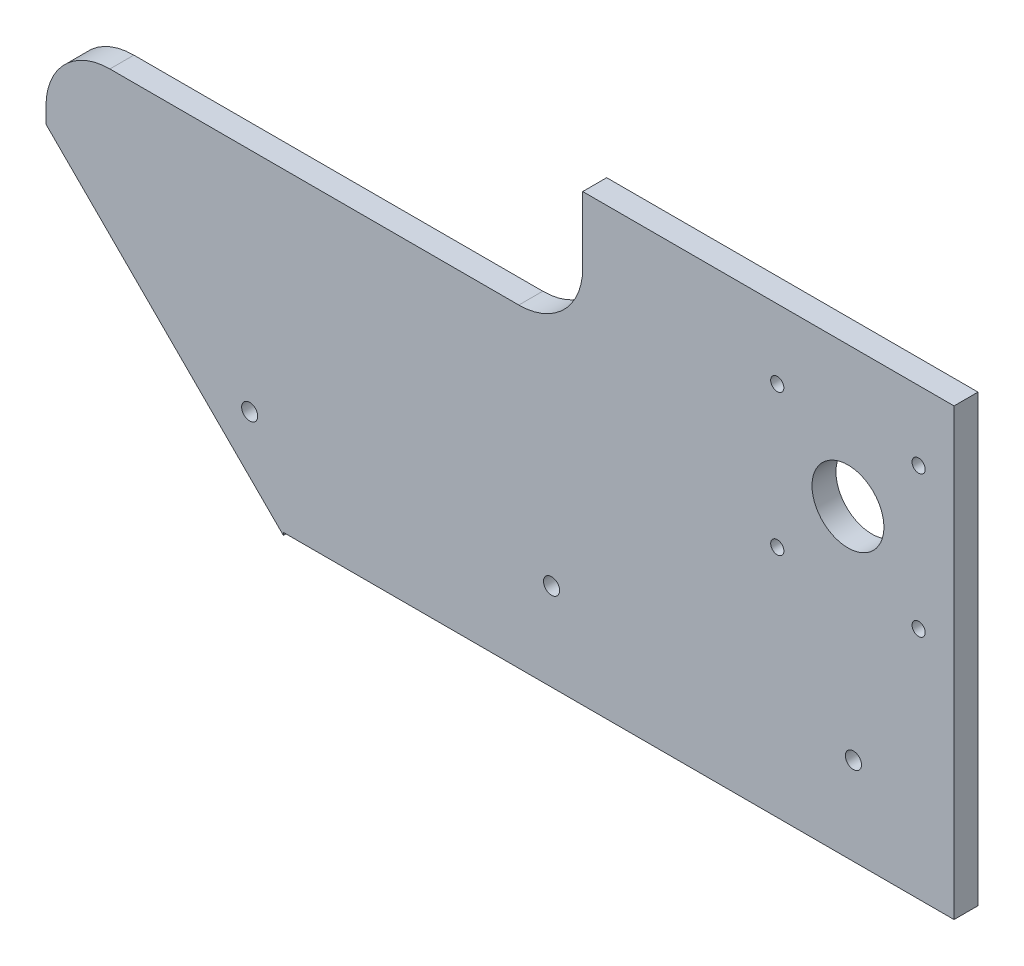
SolidWorks part; units mm, degrees
ref_plane "Front Plane" through (0, 0, 0) normal (0, 0, 1) x (1, 0, 0)
ref_plane "Top Plane" through (0, 0, 0) normal (0, 1, 0) x (1, 0, 0)
ref_plane "Right Plane" through (0, 0, 0) normal (1, 0, 0) x (0, 0, -1)
sketch "Sketch1" plane through (0, 0, 0) normal (0, 0, 1) x (1, 0, 0)
  line L0 (-138.2594, 48.9915) -> (32.2106, -121.4785)
  line L1 (32.2106, -121.4785) -> (222.7106, -121.4785)
  line L2 (-138.2594, 146.2068) -> (-138.2594, 48.9915)
  line L3 (-138.2594, 146.2068) -> (222.7106, 146.2068)
  line L4 (222.7106, -121.4785) -> (222.7106, 146.2068)
  circle A0 centre (180.538, 76.832) radius 14.2875
  circle A2 centre (180.538, 76.832) radius 69.85 construction
  circle A3 centre (180.538, 76.832) radius 318.7974 construction
  point P0 (0, 0)
  point P2 (180.538, 76.832)
  dimension "D4" = 198.3105
  dimension "D1" = 45
  dimension "D2" = 267.6854
  dimension "D5" = 245.11
extrude "Boss-Extrude1" add sketch "Sketch1" along normal blind 9.525
sketch "Sketch2" plane through (0, 0, 9.525) normal (0, 0, 1) x (1, 0, 0)
  line L0 (32.2106, -121.4785) -> (222.7106, -121.4785) construction
  line L1 (241.7606, -121.4785) -> (-43.8796, -121.4785)
  line L2 (241.7606, -121.4785) -> (241.7606, -44.3222)
  line L3 (241.7606, -44.3222) -> (-43.8796, -44.3222)
  line L4 (-43.8796, -121.4785) -> (-43.8796, -44.3222)
extrude "Cut-Extrude1" cut sketch "Sketch2" against normal through all contours L3 L4 L1 L2
sketch "Sketch4" plane through (0, 0, 9.525) normal (0, 0, 1) x (1, 0, 0)
  line L1 (-138.2594, 146.2068) -> (-138.2594, 48.9915) construction
  line L3 (-138.2594, 146.2068) -> (75.1006, 146.2068)
  line L4 (-138.2594, 146.2068) -> (-138.2594, 80.7415)
  line L5 (-138.2594, 80.7415) -> (75.1006, 80.7415)
  line L6 (75.1006, 146.2068) -> (75.1006, 80.7415)
extrude "Cut-Extrude2" cut sketch "Sketch4" against normal through all contours L5 L6 L3 L4
fillet "Fillet2" radius 25.4 2 edges at (-138.2594, 80.7415, 4.7625) (75.1006, 80.7415, 4.7625)
sketch "Sketch16" plane through (222.7106, 0, 0) normal (1, 0, 0) x (0, 0, -1)
  line L0 (0, -44.3222) -> (0, 146.2068) construction
  line L1 (-9.525, 146.2068) -> (0, 146.2068)
  line L2 (-9.525, 146.2068) -> (-9.525, 145.2215)
  line L3 (-9.525, 145.2215) -> (0, 145.2215)
  line L4 (0, 146.2068) -> (0, 145.2215)
extrude "Cut-Extrude3" cut sketch "Sketch16" against normal through all
sketch "Sketch17" plane through (0, 0, 0) normal (0, 0, -1) x (-1, 0, 0)
  line L0 (-222.7106, -44.3222) -> (-222.7106, 145.2215) construction
  line L1 (-75.1006, 145.2215) -> (-222.7106, 145.2215)
  line L2 (-75.1006, 145.2215) -> (-75.1006, 132.5215)
  line L3 (-75.1006, 132.5215) -> (-222.7106, 132.5215)
  line L4 (-222.7106, 145.2215) -> (-222.7106, 132.5215)
  dimension "D1" = 12.7
extrude "Cut-Extrude4" cut sketch "Sketch17" against normal through all
hole_wizard "Tap Drill for M6x0.75 Tap1" positions "Sketch19" profile "Sketch18" hole size "M6x0.75" standard "Lanco STD" end condition through all
sketch "Sketch19" plane through (0, 0, 9.525) normal (0, 0, 1) x (1, 0, 0)
  point P0 (208.638, 104.932)
  point P3 (152.438, 104.932)
  point P6 (152.438, 48.732)
  point P9 (208.638, 48.732)
sketch "Sketch18" plane through (208.638, 104.932, 9.525) normal (1, 0, 0) x (0, -1, 0)
  line L0 (0, 0) -> (0, 9.525)
  line L1 (0, 9.525) -> (2.625, 9.525)
  line L2 (2.625, 9.525) -> (2.625, 0)
  line L5 (2.625, 0) -> (0, 0)
  line L11 (0, -6.35) -> (0, 107.95) construction
  dimension "Thru Hole Dia." = 5.25
  dimension "Thru Hole Depth" = 9.525
hole_wizard "Ø6.4 (6.4) Diameter Hole1" positions "Sketch21" profile "Sketch20" hole size "Ø6.4" standard "ANSI Metric" end condition through all
sketch "Sketch21" plane through (0, 0, 9.525) normal (0, 0, 1) x (1, 0, 0)
  point P0 (-57.2894, -9.4645)
  point P2 (62.7106, -9.4645)
  point P4 (182.7106, -9.4645)
sketch "Sketch20" plane through (-57.2894, -9.4645, 9.525) normal (1, 0, 0) x (0, -1, 0)
  line L0 (0, 0) -> (0, 9.525)
  line L1 (0, 9.525) -> (3.2, 9.525)
  line L2 (3.2, 9.525) -> (3.2, 0)
  line L5 (3.2, 0) -> (0, 0)
  line L11 (0, -6.35) -> (0, 107.95) construction
  dimension "Thru Hole Dia." = 6.4
  dimension "Thru Hole Depth" = 9.525
